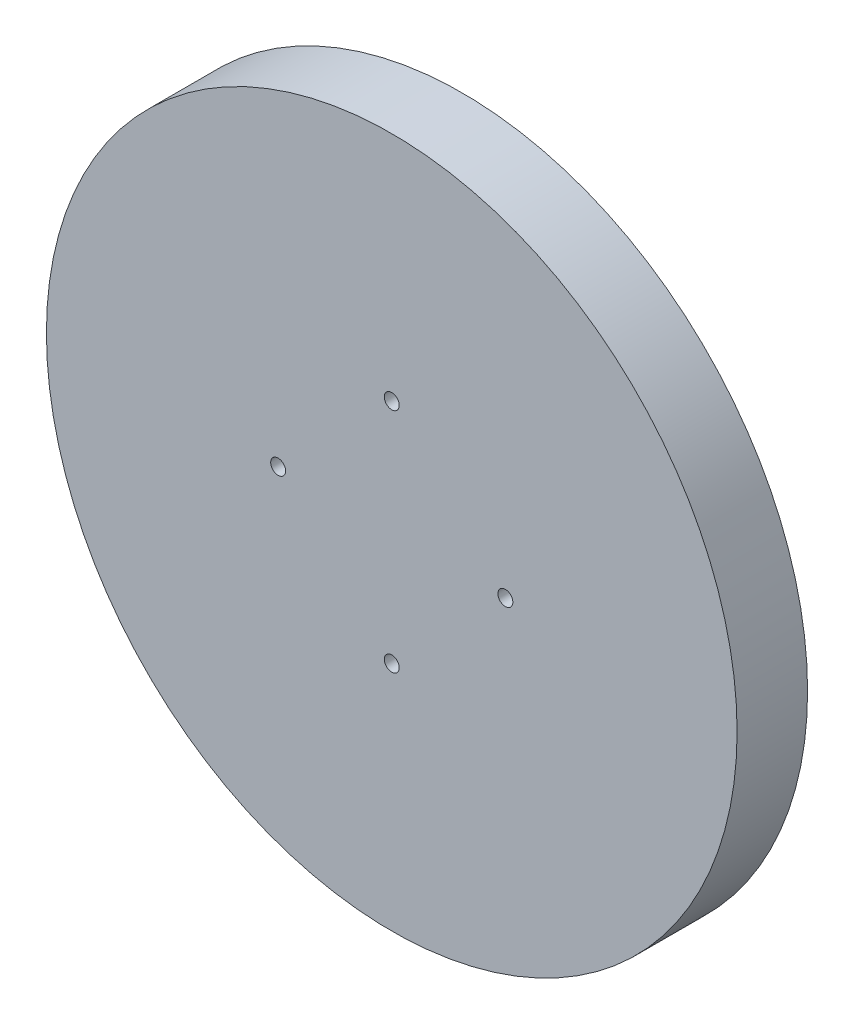
SolidWorks part; units mm, degrees
ref_plane "Plan de face" through (0, 0, 0) normal (0, 0, 1) x (1, 0, 0)
ref_plane "Plan de dessus" through (0, 0, 0) normal (0, 1, 0) x (1, 0, 0)
ref_plane "Plan de droite" through (0, 0, 0) normal (1, 0, 0) x (0, 0, -1)
sketch "Esquisse1" plane through (0, 0, 0) normal (0, 0, 1) x (1, 0, 0)
  circle A0 centre (0, 0) radius 24.5
  dimension "D1" = 49
extrude "Boss.-Extru.1" add sketch "Esquisse1" along normal blind 5
sketch "Esquisse2" plane through (0, 0, 5) normal (0, 0, 1) x (1, 0, 0)
  line L0 (0, 0) -> (0, 2.1842) construction
  circle A0 centre (0, 8.06) radius 0.53
  dimension "D2" = 1.06
  dimension "D1" = 8.06
extrude "Enlèv. mat.-Extru.1" cut sketch "Esquisse2" against normal up to surface (5 mm away) up to face at (24.5, 0, 0)
pattern_circular "Répétition circulaire1" count 4 over 360 about axis through (0, 0, 0) along (0, 0, 1) of "Enlèv. mat.-Extru.1"
